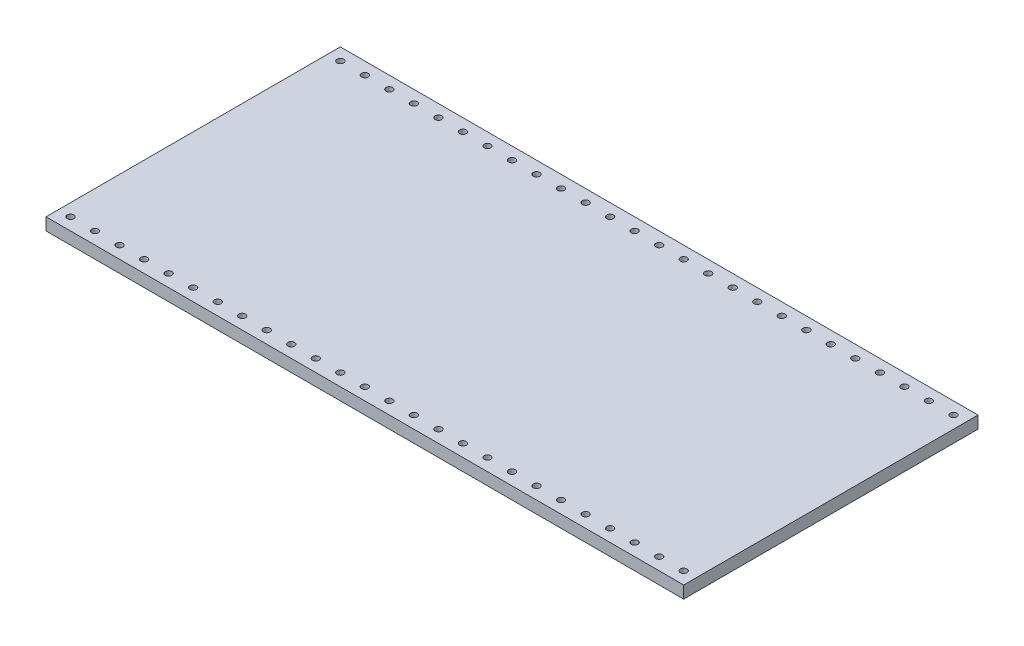
SolidWorks part; units mm, degrees
ref_plane "Front Plane" through (0, 0, 0) normal (0, 0, 1) x (1, 0, 0)
ref_plane "Top Plane" through (0, 0, 0) normal (0, 1, 0) x (1, 0, 0)
ref_plane "Right Plane" through (0, 0, 0) normal (1, 0, 0) x (0, 0, -1)
sketch "Sketch1" plane through (0, 0, 0) normal (0, 1, 0) x (1, 0, 0)
  line L1 (-330.2, -152.4) -> (330.2, -152.4)
  line L2 (-330.2, -152.4) -> (-330.2, 152.4)
  line L3 (-330.2, 152.4) -> (330.2, 152.4)
  line L4 (330.2, -152.4) -> (330.2, 152.4)
  line L5 (0, 152.4) -> (0, -152.4) construction
  line L6 (-330.2, 0) -> (330.2, 0) construction
  circle A0 centre (-317.5, 139.7) radius 3.429
  circle A1 centre (-292.1, 139.7) radius 3.429
  circle A2 centre (-266.7, 139.7) radius 3.429
  circle A3 centre (-241.3, 139.7) radius 3.429
  circle A4 centre (-215.9, 139.7) radius 3.429
  circle A5 centre (-190.5, 139.7) radius 3.429
  circle A6 centre (-165.1, 139.7) radius 3.429
  circle A7 centre (-139.7, 139.7) radius 3.429
  circle A8 centre (-114.3, 139.7) radius 3.429
  circle A9 centre (-88.9, 139.7) radius 3.429
  circle A10 centre (-63.5, 139.7) radius 3.429
  circle A11 centre (-38.1, 139.7) radius 3.429
  circle A12 centre (-12.7, 139.7) radius 3.429
  circle A13 centre (12.7, 139.7) radius 3.429
  circle A14 centre (38.1, 139.7) radius 3.429
  circle A15 centre (63.5, 139.7) radius 3.429
  circle A16 centre (88.9, 139.7) radius 3.429
  circle A17 centre (114.3, 139.7) radius 3.429
  circle A18 centre (139.7, 139.7) radius 3.429
  circle A19 centre (165.1, 139.7) radius 3.429
  circle A20 centre (190.5, 139.7) radius 3.429
  circle A21 centre (215.9, 139.7) radius 3.429
  circle A22 centre (241.3, 139.7) radius 3.429
  circle A23 centre (266.7, 139.7) radius 3.429
  circle A24 centre (292.1, 139.7) radius 3.429
  circle A25 centre (317.5, 139.7) radius 3.429
  circle A26 centre (-292.1, -139.7) radius 3.429
  circle A27 centre (-266.7, -139.7) radius 3.429
  circle A28 centre (-241.3, -139.7) radius 3.429
  circle A29 centre (-215.9, -139.7) radius 3.429
  circle A30 centre (-190.5, -139.7) radius 3.429
  circle A31 centre (-165.1, -139.7) radius 3.429
  circle A32 centre (-139.7, -139.7) radius 3.429
  circle A33 centre (-114.3, -139.7) radius 3.429
  circle A34 centre (-88.9, -139.7) radius 3.429
  circle A35 centre (-63.5, -139.7) radius 3.429
  circle A36 centre (-38.1, -139.7) radius 3.429
  circle A37 centre (-12.7, -139.7) radius 3.429
  circle A38 centre (12.7, -139.7) radius 3.429
  circle A39 centre (38.1, -139.7) radius 3.429
  circle A40 centre (63.5, -139.7) radius 3.429
  circle A41 centre (88.9, -139.7) radius 3.429
  circle A42 centre (114.3, -139.7) radius 3.429
  circle A43 centre (139.7, -139.7) radius 3.429
  circle A44 centre (165.1, -139.7) radius 3.429
  circle A45 centre (190.5, -139.7) radius 3.429
  circle A46 centre (215.9, -139.7) radius 3.429
  circle A47 centre (241.3, -139.7) radius 3.429
  circle A48 centre (266.7, -139.7) radius 3.429
  circle A49 centre (292.1, -139.7) radius 3.429
  circle A50 centre (317.5, -139.7) radius 3.429
  circle A51 centre (-317.5, -139.7) radius 3.429
  point P0 (0, 0)
  dimension "D3" = 6.858
  dimension "D1" = 660.4
  dimension "D2" = 304.8
  dimension "D4" = 12.7
  dimension "D5" = 12.7
  dimension "D6" = 26
  dimension "D7" = 2
extrude "Boss-Extrude1" add sketch "Sketch1" against normal blind 12.7
